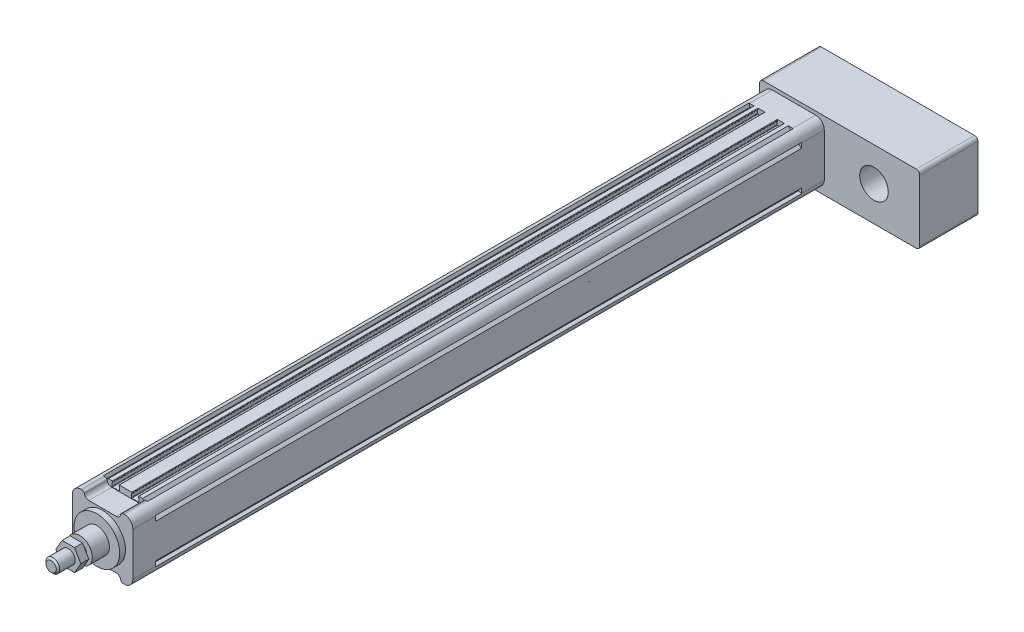
SolidWorks part; units mm, degrees
ref_plane "Front" through (0, 0, 0) normal (0, 0, 1) x (1, 0, 0)
ref_plane "Top" through (0, 0, 0) normal (0, 1, 0) x (1, 0, 0)
ref_plane "Right" through (0, 0, 0) normal (1, 0, 0) x (0, 0, -1)
sketch "草图1" plane through (0, 0, 0) normal (0, 0, 1) x (1, 0, 0)
  line L0 (19.7737, 3) -> (23.3, 3)
  line L1 (23.3, 3) -> (23.3, -3)
  line L2 (23.3, -3) -> (19.7737, -3)
  line L3 (-19.7737, -3) -> (-23.3, -3)
  line L4 (-23.3, -3) -> (-23.3, 3)
  line L5 (-23.3, 3) -> (-19.7737, 3)
  line L6 (-18.2, 24) -> (-19.4434, 26.4869)
  line L7 (-26.4869, 19.4434) -> (-24, 18.2)
  line L8 (-24, 18.2) -> (-24, 17.1)
  line L9 (-24, 17.1) -> (-26.5, 15)
  line L10 (-26.5, 15) -> (-26.5, -15)
  line L11 (-26.5, -15) -> (-24, -17.1)
  line L12 (-24, -17.1) -> (-24, -18.2)
  line L13 (-24, -18.2) -> (-26.4869, -19.4434)
  line L14 (-19.4434, -26.4869) -> (-18.2, -24)
  line L15 (-18.2, -24) -> (-17.1, -24)
  line L16 (-17.1, -24) -> (-15, -26.5)
  line L17 (-15, -26.5) -> (-11.65, -26.5)
  line L18 (-11.25, -26.1) -> (-11.25, -25.6)
  line L19 (-11.65, -25.2) -> (-11.75, -25.2)
  line L20 (-11.75, -25.2) -> (-11.75, -22.4)
  line L21 (-11.35, -22) -> (-5.65, -22)
  line L22 (-5.25, -22.4) -> (-5.25, -25.2)
  line L23 (-5.25, -25.2) -> (-5.35, -25.2)
  line L24 (-5.75, -25.6) -> (-5.75, -26.1)
  line L25 (-5.35, -26.5) -> (5.35, -26.5)
  line L26 (5.75, -26.1) -> (5.75, -25.6)
  line L27 (5.35, -25.2) -> (5.25, -25.2)
  line L28 (5.25, -25.2) -> (5.25, -22.4)
  line L29 (5.65, -22) -> (11.35, -22)
  line L30 (11.75, -22.4) -> (11.75, -25.2)
  line L31 (11.75, -25.2) -> (11.65, -25.2)
  line L32 (11.25, -25.6) -> (11.25, -26.1)
  line L33 (11.65, -26.5) -> (15, -26.5)
  line L34 (15, -26.5) -> (17.1, -24)
  line L35 (17.1, -24) -> (18.2, -24)
  line L36 (18.2, -24) -> (19.4434, -26.4869)
  line L37 (26.4869, -19.4434) -> (24, -18.2)
  line L38 (24, -18.2) -> (24, -17.1)
  line L39 (24, -17.1) -> (26.5, -15)
  line L40 (26.5, -15) -> (26.5, 15)
  line L41 (26.5, 15) -> (24, 17.1)
  line L42 (24, 17.1) -> (24, 18.2)
  line L43 (24, 18.2) -> (26.4869, 19.4434)
  line L44 (19.4434, 26.4869) -> (18.2, 24)
  line L45 (18.2, 24) -> (17.1, 24)
  line L46 (17.1, 24) -> (15, 26.5)
  line L47 (15, 26.5) -> (11.65, 26.5)
  line L48 (11.25, 26.1) -> (11.25, 25.6)
  line L49 (11.65, 25.2) -> (11.75, 25.2)
  line L50 (11.75, 25.2) -> (11.75, 22.4)
  line L51 (11.35, 22) -> (5.65, 22)
  line L52 (5.25, 22.4) -> (5.25, 25.2)
  line L53 (5.25, 25.2) -> (5.35, 25.2)
  line L54 (5.75, 25.6) -> (5.75, 26.1)
  line L55 (5.35, 26.5) -> (-5.35, 26.5)
  line L56 (-5.75, 26.1) -> (-5.75, 25.6)
  line L57 (-5.35, 25.2) -> (-5.25, 25.2)
  line L58 (-5.25, 25.2) -> (-5.25, 22.4)
  line L59 (-5.65, 22) -> (-11.35, 22)
  line L60 (-11.75, 22.4) -> (-11.75, 25.2)
  line L61 (-11.75, 25.2) -> (-11.65, 25.2)
  line L62 (-11.25, 25.6) -> (-11.25, 26.1)
  line L63 (-11.65, 26.5) -> (-15, 26.5)
  line L64 (-15, 26.5) -> (-17.1, 24)
  line L65 (-17.1, 24) -> (-18.2, 24)
  arc A0 (19.7737, 3) -> (-19.7737, 3) centre (0, 0) ccw
  arc A1 (-19.7737, -3) -> (19.7737, -3) centre (0, 0) ccw
  circle A2 centre (19, 19) radius 2.1
  circle A3 centre (19, -19) radius 2.1
  circle A4 centre (-19, -19) radius 2.1
  circle A5 centre (-19, 19) radius 2.1
  arc A6 (-19.4434, 26.4869) -> (-26.4869, 19.4434) centre (-19, 19) ccw
  arc A7 (-26.4869, -19.4434) -> (-19.4434, -26.4869) centre (-19, -19) ccw
  arc A8 (-11.65, -26.5) -> (-11.25, -26.1) centre (-11.65, -26.1) ccw
  arc A9 (-11.25, -25.6) -> (-11.65, -25.2) centre (-11.65, -25.6) ccw
  arc A10 (-11.35, -22) -> (-11.75, -22.4) centre (-11.35, -22.4) ccw
  arc A11 (-5.25, -22.4) -> (-5.65, -22) centre (-5.65, -22.4) ccw
  arc A12 (-5.35, -25.2) -> (-5.75, -25.6) centre (-5.35, -25.6) ccw
  arc A13 (-5.75, -26.1) -> (-5.35, -26.5) centre (-5.35, -26.1) ccw
  arc A14 (5.35, -26.5) -> (5.75, -26.1) centre (5.35, -26.1) ccw
  arc A15 (5.75, -25.6) -> (5.35, -25.2) centre (5.35, -25.6) ccw
  arc A16 (5.65, -22) -> (5.25, -22.4) centre (5.65, -22.4) ccw
  arc A17 (11.75, -22.4) -> (11.35, -22) centre (11.35, -22.4) ccw
  arc A18 (11.65, -25.2) -> (11.25, -25.6) centre (11.65, -25.6) ccw
  arc A19 (11.25, -26.1) -> (11.65, -26.5) centre (11.65, -26.1) ccw
  arc A20 (19.4434, -26.4869) -> (26.4869, -19.4434) centre (19, -19) ccw
  arc A21 (26.4869, 19.4434) -> (19.4434, 26.4869) centre (19, 19) ccw
  arc A22 (11.65, 26.5) -> (11.25, 26.1) centre (11.65, 26.1) ccw
  arc A23 (11.25, 25.6) -> (11.65, 25.2) centre (11.65, 25.6) ccw
  arc A24 (11.35, 22) -> (11.75, 22.4) centre (11.35, 22.4) ccw
  arc A25 (5.25, 22.4) -> (5.65, 22) centre (5.65, 22.4) ccw
  arc A26 (5.35, 25.2) -> (5.75, 25.6) centre (5.35, 25.6) ccw
  arc A27 (5.75, 26.1) -> (5.35, 26.5) centre (5.35, 26.1) ccw
  arc A28 (-5.35, 26.5) -> (-5.75, 26.1) centre (-5.35, 26.1) ccw
  arc A29 (-5.75, 25.6) -> (-5.35, 25.2) centre (-5.35, 25.6) ccw
  arc A30 (-5.65, 22) -> (-5.25, 22.4) centre (-5.65, 22.4) ccw
  arc A31 (-11.75, 22.4) -> (-11.35, 22) centre (-11.35, 22.4) ccw
  arc A32 (-11.65, 25.2) -> (-11.25, 25.6) centre (-11.65, 25.6) ccw
  arc A33 (-11.25, 26.1) -> (-11.65, 26.5) centre (-11.65, 26.1) ccw
extrude "凸台-拉伸1" add sketch "草图1" along normal blind 565
sketch "草图6" plane through (0, 0, 565) normal (0, 0, 1) x (1, 0, 0)
  line L0 (0, 0) -> (19, 0) construction
  line L2 (-26.5, -19) -> (-26.5, 19)
  line L3 (-19, 26.5) -> (-17.9161, 26.5)
  line L4 (26.5, -19) -> (26.5, 19)
  line L5 (-26.5, -26.5) -> (26.5, 26.5) construction
  line L6 (-26.5, 26.5) -> (26.5, -26.5) construction
  line L7 (-12, 21.5) -> (12, 21.5)
  line L9 (19, 26.5) -> (17.9161, 26.5)
  line L10 (19, -26.5) -> (17.9161, -26.5)
  line L11 (-12, -21.5) -> (12, -21.5)
  line L12 (-19, -26.5) -> (-17.9161, -26.5)
  arc A0 (12, 21.5) -> (15.9441, 24.8333) centre (12, 25.5) ccw
  arc A1 (-15.9441, 24.8333) -> (-12, 21.5) centre (-12, 25.5) ccw
  arc A2 (-15.9441, 24.8333) -> (-17.9161, 26.5) centre (-17.9161, 24.5) ccw
  arc A3 (15.9441, 24.8333) -> (17.9161, 26.5) centre (17.9161, 24.5) cw
  arc A4 (-26.5, -19) -> (-19, -26.5) centre (-19, -19) ccw
  arc A5 (19, -26.5) -> (26.5, -19) centre (19, -19) ccw
  arc A6 (26.5, 19) -> (19, 26.5) centre (19, 19) ccw
  arc A7 (-26.5, 19) -> (-19, 26.5) centre (-19, 19) cw
  arc A8 (15.9441, -24.8333) -> (17.9161, -26.5) centre (17.9161, -24.5) ccw
  arc A9 (12, -21.5) -> (15.9441, -24.8333) centre (12, -25.5) cw
  arc A10 (-15.9441, -24.8333) -> (-12, -21.5) centre (-12, -25.5) cw
  arc A11 (-15.9441, -24.8333) -> (-17.9161, -26.5) centre (-17.9161, -24.5) cw
  point P0 (0, 0)
  point P9 (0, 21.5)
  point P13 (20, 20.8461)
  point P16 (-12, 20.8461)
  dimension "D5" = 4
  dimension "D6" = 2
  dimension "D7" = 2
  dimension "D9" = 7.5
  dimension "D1" = 53
  dimension "D2" = 53
  dimension "D3" = 26.5
  dimension "D4" = 24
  dimension "D8" = 5
extrude "凸台-拉伸2" add sketch "草图6" along normal blind 20
sketch "草图7" plane through (0, 0, 585) normal (0, 0, 1) x (1, 0, 0)
  circle A0 centre (0, 0) radius 20
  dimension "D1" = 40
extrude "凸台-拉伸3" add sketch "草图7" along normal blind 5
sketch "草图9" plane through (0, 0, 590) normal (0, 0, 1) x (1, 0, 0)
  circle A0 centre (0, 0) radius 11
  dimension "D1" = 22
extrude "凸台-拉伸4" add sketch "草图9" along normal blind 15
sketch "草图10" plane through (0, 0, 605) normal (0, 0, 1) x (1, 0, 0)
  circle A0 centre (0, 0) radius 6
  dimension "D1" = 12
extrude "凸台-拉伸5" add sketch "草图10" along normal blind 25
sketch "草图11" plane through (0, 0, 0) normal (0, 0, -1) x (-1, 0, 0)
  line L1 (-19, -26.5) -> (19, -26.5)
  line L2 (-26.5, -19) -> (-26.5, 19)
  line L3 (-19, 26.5) -> (19, 26.5)
  line L4 (26.5, -19) -> (26.5, 19)
  line L5 (-26.5, -26.5) -> (26.5, 26.5) construction
  line L6 (-26.5, 26.5) -> (26.5, -26.5) construction
  arc A0 (-26.5, -19) -> (-19, -26.5) centre (-19, -19) ccw
  arc A1 (19, -26.5) -> (26.5, -19) centre (19, -19) ccw
  arc A2 (26.5, 19) -> (19, 26.5) centre (19, 19) ccw
  arc A3 (-26.5, 19) -> (-19, 26.5) centre (-19, 19) cw
  point P0 (0, 0)
  dimension "D3" = 7.5
  dimension "D1" = 53
  dimension "D2" = 53
extrude "凸台-拉伸6" add sketch "草图11" along normal blind 20
sketch "草图12" plane through (0, 0, -20) normal (0, 0, -1) x (-1, 0, 0)
  line L1 (-107, -30.4042) -> (27, -30.4042)
  line L2 (-110, -27.4042) -> (-110, 26.5958)
  line L3 (-107, 29.5958) -> (27, 29.5958)
  line L4 (30, -27.4042) -> (30, 26.5958)
  line L5 (-110, -30.4042) -> (30, 29.5958) construction
  line L6 (-110, 29.5958) -> (30, -30.4042) construction
  arc A0 (27, 29.5958) -> (30, 26.5958) centre (27, 26.5958) cw
  arc A1 (30, -27.4042) -> (27, -30.4042) centre (27, -27.4042) cw
  arc A2 (-110, -27.4042) -> (-107, -30.4042) centre (-107, -27.4042) ccw
  arc A3 (-110, 26.5958) -> (-107, 29.5958) centre (-107, 26.5958) cw
  point P0 (-40, -0.4042)
  dimension "D4" = 3
  dimension "D1" = 60
  dimension "D2" = 140
  dimension "D3" = 30
extrude "凸台-拉伸7" add sketch "草图12" along normal blind 51
sketch "草图13" plane through (0, 0, -20) normal (0, 0, 1) x (1, 0, 0)
  circle A0 centre (70, 0) radius 12.5
  dimension "D2" = 25
  dimension "D1" = 70
extrude "切除-拉伸2" cut sketch "草图13" against normal blind 30
hole_wizard "M6 螺纹孔1" positions "草图14" profile "草图15" tap size "M6" standard "GB"
sketch "草图14" plane through (0, 0, -71) normal (0, 0, -1) x (-1, 0, 0)
  line L0 (30, -27.4042) -> (30, 26.5958) construction
  point P0 (19, -19)
  dimension "D1" = 11
  dimension "D2" = 19
sketch "草图15" plane through (-19, -19, -71) normal (1, 0, 0) x (0, 1, 0)
  line L0 (0, 0) -> (0, 16.5022)
  line L1 (0, 16.5022) -> (2.5, 15)
  line L2 (2.5, 15) -> (2.5, 0)
  line L5 (2.5, 0) -> (0, 0)
  line L10 (0, 16.5022) -> (-2.5, 15) construction
  line L11 (0, -6.35) -> (0, 107.95) construction
  dimension "螺纹孔钻头直径" = 5
  dimension "螺纹孔钻头深度" = 15
  dimension "导头角度" = 118
cosmetic thread "孔螺蚊线4" parameters "D1"=12, "D2"=6
pattern_linear "阵列(线性)1" count 2 spacing 38 along (0, 1, 0) count 2 spacing 38 along (1, 0, 0) of "M6 螺纹孔1"
hole_wizard "M6 螺纹孔2" positions "草图16" profile "草图17" tap size "M6" standard "GB"
sketch "草图16" plane through (0, 0, -71) normal (0, 0, -1) x (-1, 0, 0)
  circle A1 centre (-19, 19) radius 2.5 construction
  circle A2 centre (-19, -19) radius 2.5 construction
  point P0 (-84, -19)
  point P2 (-84, 19)
  dimension "D3" = 65
  dimension "D1" = 19
  dimension "D2" = 19
  dimension "D4" = 65
sketch "草图17" plane through (84, -19, -71) normal (1, 0, 0) x (0, 1, 0)
  line L0 (0, 0) -> (0, 16.5022)
  line L1 (0, 16.5022) -> (2.5, 15)
  line L2 (2.5, 15) -> (2.5, 0)
  line L5 (2.5, 0) -> (0, 0)
  line L10 (0, 16.5022) -> (-2.5, 15) construction
  line L11 (0, -6.35) -> (0, 107.95) construction
  dimension "螺纹孔钻头直径" = 5
  dimension "螺纹孔钻头深度" = 15
  dimension "导头角度" = 118
cosmetic thread "孔螺蚊线5" parameters "D1"=12, "D2"=6
cosmetic thread "孔螺蚊线6" parameters "D1"=12, "D2"=6
hole_wizard "M6 螺纹孔3" positions "草图19" profile "草图20" tap size "M6" standard "GB"
sketch "草图19" plane through (-26.5, 0, 0) normal (-1, 0, 0) x (0, 0, 1)
  line L0 (585, 19) -> (585, -19) construction
  point P0 (575, 11)
  point P2 (575, -11)
  dimension "D1" = 10
  dimension "D2" = 10
  dimension "D3" = 22
  dimension "D4" = 11
sketch "草图20" plane through (-26.5, 11, 575) normal (0, 1, 0) x (0, 0, 1)
  line L0 (0, 0) -> (0, 16.5022)
  line L1 (0, 16.5022) -> (2.5, 15)
  line L2 (2.5, 15) -> (2.5, 0)
  line L5 (2.5, 0) -> (0, 0)
  line L10 (0, 16.5022) -> (-2.5, 15) construction
  line L11 (0, -6.35) -> (0, 107.95) construction
  dimension "螺纹孔钻头直径" = 5
  dimension "螺纹孔钻头深度" = 15
  dimension "导头角度" = 118
cosmetic thread "孔螺蚊线7" parameters "D1"=12, "D2"=6
cosmetic thread "孔螺蚊线8" parameters "D1"=12, "D2"=6
hole_wizard "M6 螺纹孔4" positions "草图21" profile "草图22" tap size "M6" standard "GB"
sketch "草图21" plane through (-26.5, 0, 0) normal (-1, 0, 0) x (0, 0, 1)
  line L0 (-20, -27.4042) -> (-20, 26.5958) construction
  line L1 (-20, -19) -> (-20, 19) construction
  point P0 (-10, 11)
  point P2 (-10, -11)
  dimension "D1" = 10
  dimension "D2" = 10
  dimension "D3" = 11
  dimension "D4" = 11
sketch "草图22" plane through (-26.5, 11, -10) normal (0, 1, 0) x (0, 0, 1)
  line L0 (0, 0) -> (0, 16.5022)
  line L1 (0, 16.5022) -> (2.5, 15)
  line L2 (2.5, 15) -> (2.5, 0)
  line L5 (2.5, 0) -> (0, 0)
  line L10 (0, 16.5022) -> (-2.5, 15) construction
  line L11 (0, -6.35) -> (0, 107.95) construction
  dimension "螺纹孔钻头直径" = 5
  dimension "螺纹孔钻头深度" = 15
  dimension "导头角度" = 118
cosmetic thread "孔螺蚊线9" parameters "D1"=12, "D2"=6
cosmetic thread "孔螺蚊线10" parameters "D1"=12, "D2"=6
chamfer "倒角1" distance 1.5 angle 45 1 edges at (6, 0, 630)
sketch "草图23" plane through (0, 0, 605) normal (0, 0, 1) x (1, 0, 0)
  line L1 (10.9697, 0) -> (5.4848, 9.5)
  line L2 (5.4848, 9.5) -> (-5.4848, 9.5)
  line L3 (-5.4848, 9.5) -> (-10.9697, 0)
  line L4 (-10.9697, 0) -> (-5.4848, -9.5)
  line L5 (-5.4848, -9.5) -> (5.4848, -9.5)
  line L6 (5.4848, -9.5) -> (10.9697, 0)
  circle A0 centre (0, 0) radius 9.5 construction
  dimension "D1" = 19
extrude "凸台-拉伸8" add sketch "草图23" along normal blind 7 from offset 3
